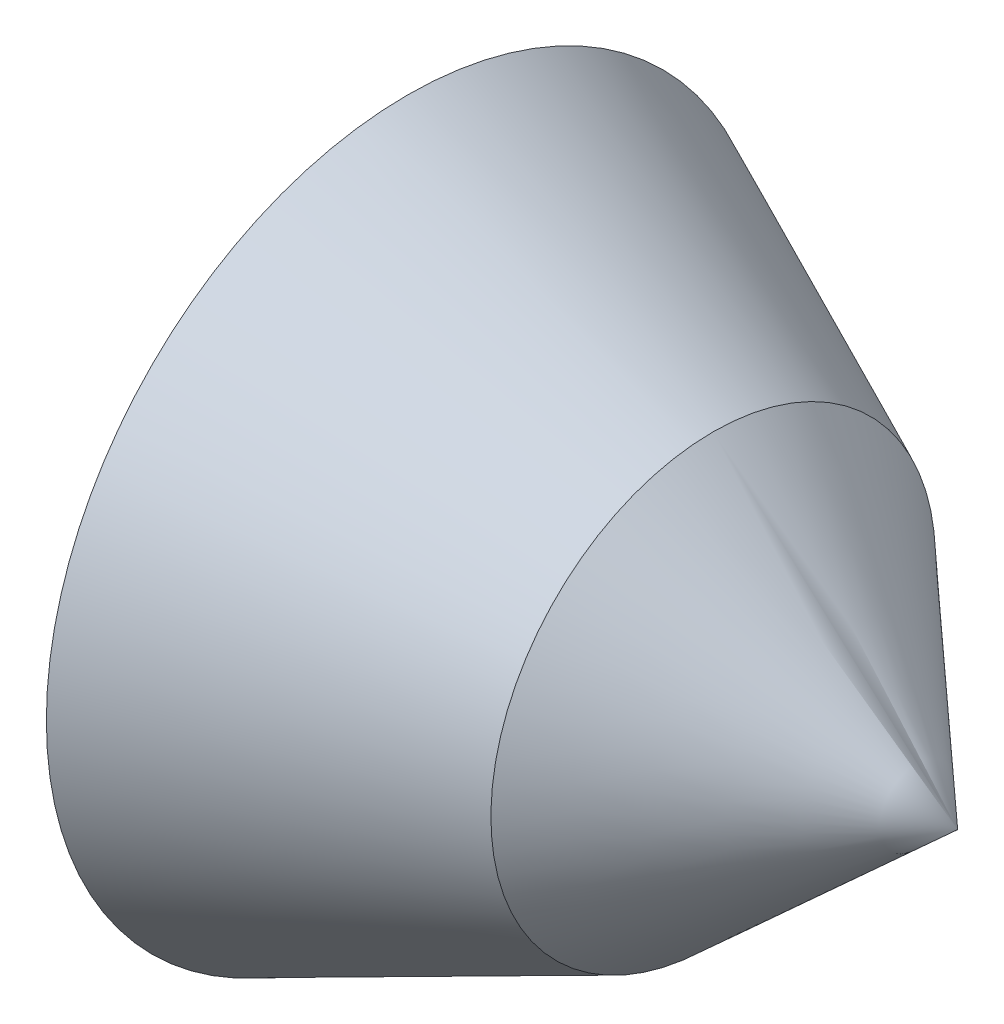
SolidWorks part; units mm, degrees
ref_plane "Front Plane" through (0, 0, 0) normal (0, 0, 1) x (1, 0, 0)
ref_plane "Top Plane" through (0, 0, 0) normal (0, 1, 0) x (1, 0, 0)
ref_plane "Right Plane" through (0, 0, 0) normal (1, 0, 0) x (0, 0, -1)
sketch "Sketch1" plane through (0, 0, 0) normal (0, 0, 1) x (1, 0, 0)
  line L0 (0, 0) -> (8000, 0) construction
  line L1 (6300, 350) -> (6300, 650)
  line L2 (6300, 650) -> (6850, 400)
  line L3 (6850, 400) -> (7290, 0)
  line L4 (7290, 0) -> (6300, 0)
  line L5 (6300, 0) -> (6300, 350)
revolve "Revolve1" add sketch "Sketch1" angle 360 about L0
